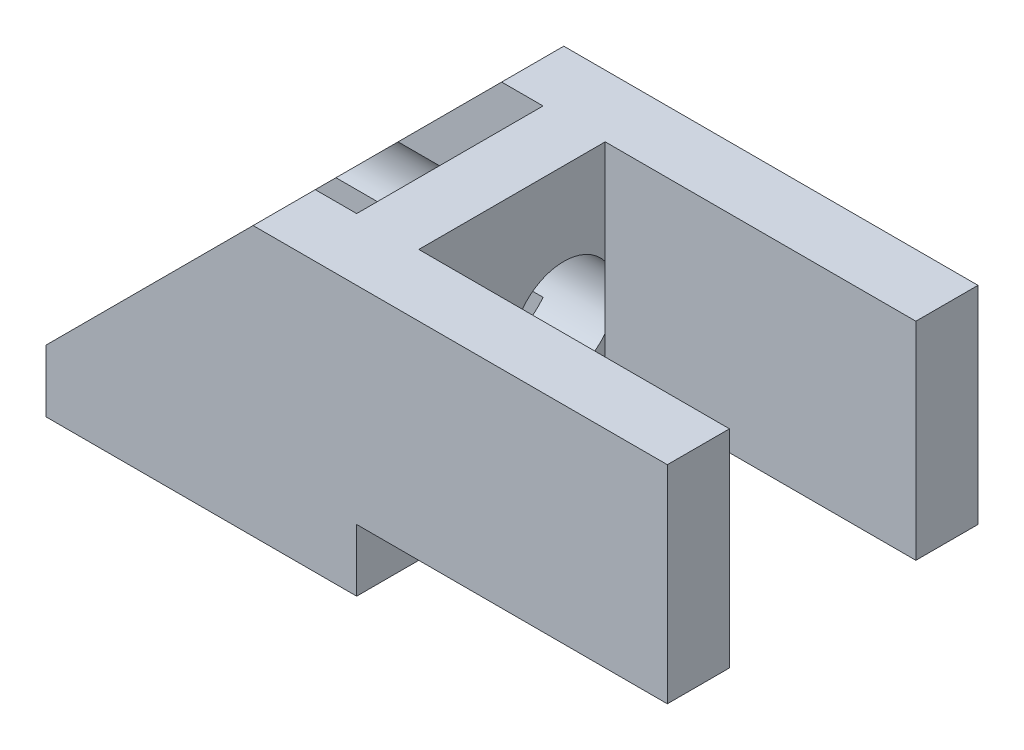
SolidWorks part; units mm, degrees
ref_plane "Front Plane" through (0, 0, 0) normal (0, 0, 1) x (1, 0, 0)
ref_plane "Top Plane" through (0, 0, 0) normal (0, 1, 0) x (1, 0, 0)
ref_plane "Right Plane" through (0, 0, 0) normal (1, 0, 0) x (0, 0, -1)
sketch "Sketch2" plane through (0, 0, 0) normal (0, 1, 0) x (1, 0, 0)
  line L1 (0, 0) -> (15, 0)
  line L2 (0, 0) -> (0, 15)
  line L3 (0, 15) -> (15, 15)
  line L4 (15, 0) -> (15, 15)
  dimension "D1" = 15
  dimension "D2" = 15
extrude "Boss-Extrude1" add sketch "Sketch2" along normal blind 3
sketch "Sketch3" plane through (0, 0, 0) normal (0, 0, 1) x (1, 0, 0)
  line L0 (0, 3) -> (10, 13)
  line L1 (10, 13) -> (30, 13)
  line L2 (30, 13) -> (30, 3)
  line L3 (0, 3) -> (15, 3) construction
  line L4 (30, 3) -> (0, 3)
  dimension "D1" = 20
  dimension "D2" = 30
  dimension "D3" = 10
extrude "Boss-Extrude2" add sketch "Sketch3" against normal blind 3
ref_plane "Plane1" through (0, 0, -7.5) normal (0, 0, 1) x (1, 0, 0)
mirror "Mirror1" about plane through (0, 0, -7.5) normal (0, 0, 1) of "Boss-Extrude1", "Boss-Extrude2"
sketch "Sketch5" plane through (15, 0, 0) normal (1, 0, 0) x (0, 0, -1)
  line L1 (3, 13) -> (12, 13)
  line L2 (3, 13) -> (3, 3)
  line L3 (3, 3) -> (12, 3)
  line L4 (12, 13) -> (12, 3)
extrude "Boss-Extrude4" add sketch "Sketch5" against normal blind 3
sketch "Sketch6" plane through (15, 0, 0) normal (1, 0, 0) x (0, 0, -1)
  line L0 (10, 0) -> (10, 13) construction
  line L1 (7.5, 7.15) -> (7.5, -7.15) construction
  line L2 (3, 13) -> (0, 13) construction
  line L3 (0, 0) -> (15, 0) construction
  circle A0 centre (10, 6.5) radius 2.5
  dimension "D1" = 5
  dimension "D2" = 6.5
extrude "Cut-Extrude1" cut sketch "Sketch6" against normal up to next
